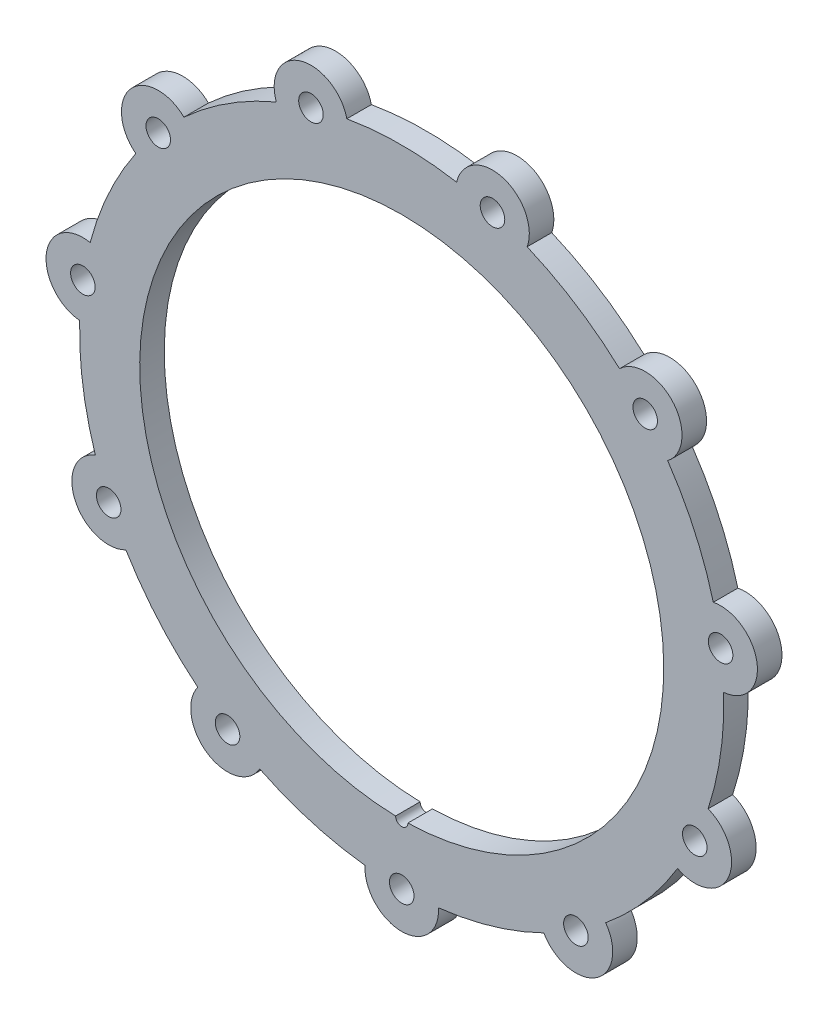
SolidWorks part; units mm, degrees
ref_plane "前视基准面" through (0, 0, 0) normal (0, 0, 1) x (1, 0, 0)
ref_plane "上视基准面" through (0, 0, 0) normal (0, 1, 0) x (1, 0, 0)
ref_plane "右视基准面" through (0, 0, 0) normal (1, 0, 0) x (0, 0, -1)
sketch "草图1" plane through (0, 0, 0) normal (0, 0, 1) x (1, 0, 0)
  line L0 (0, 0) -> (-51.9656, 7.4715) construction
  line L1 (-51.9656, 7.4715) -> (-73.6711, 10.5923) construction
  line L2 (0, 0) -> (-47.7557, -21.8093) construction
  line L3 (-47.7557, -21.8093) -> (-59.3488, -27.1037) construction
  circle A0 centre (0, 0) radius 42.7
  circle A1 centre (0, 0) radius 62.5 construction
  circle A2 centre (0, 0) radius 59 construction
  circle A19 centre (0, 0) radius 52.5 construction
  circle A23 centre (-51.9656, 7.4715) radius 2
  circle A103 centre (-47.7557, -21.8093) radius 6 construction
  circle A104 centre (-51.9656, 7.4715) radius 6 construction
  arc A105 (-57.9046, 8.3254) -> (-52.4788, 1.4935) centre (-51.9656, 7.4715) ccw
  arc A106 (-49.9322, -16.218) -> (-53.2135, -24.3018) centre (-47.7557, -21.8093) ccw
  arc A107 (-49.9322, -16.218) -> (-52.4788, 1.4935) centre (0, 0) cw
  arc A108 (-44.2114, 38.3094) -> (-43.3405, 29.6286) centre (-39.6769, 34.3802) ccw
  arc A109 (-50.7738, 13.352) -> (-43.3405, 29.6286) centre (0, 0) cw
  arc A110 (-50.7738, 13.352) -> (-57.9046, 8.3254) centre (-51.9656, 7.4715) ccw
  circle A111 centre (-39.6769, 34.3802) radius 2
  arc A112 (-16.4814, 56.1303) -> (-20.4419, 48.3568) centre (-14.791, 50.3734) ccw
  arc A113 (-35.495, 38.6828) -> (-20.4419, 48.3568) centre (0, 0) cw
  arc A114 (-35.495, 38.6828) -> (-44.2114, 38.3094) centre (-39.6769, 34.3802) ccw
  circle A115 centre (-14.791, 50.3734) radius 2
  arc A116 (16.4814, 56.1303) -> (8.9468, 51.732) centre (14.791, 50.3734) ccw
  arc A117 (-8.9468, 51.732) -> (8.9468, 51.732) centre (0, 0) cw
  arc A118 (-8.9468, 51.732) -> (-16.4814, 56.1303) centre (-14.791, 50.3734) ccw
  circle A119 centre (14.791, 50.3734) radius 2
  arc A120 (44.2114, 38.3094) -> (35.495, 38.6828) centre (39.6769, 34.3802) ccw
  arc A121 (20.4419, 48.3568) -> (35.495, 38.6828) centre (0, 0) cw
  arc A122 (20.4419, 48.3568) -> (16.4814, 56.1303) centre (14.791, 50.3734) ccw
  circle A123 centre (39.6769, 34.3802) radius 2
  arc A124 (57.9046, 8.3254) -> (50.7738, 13.352) centre (51.9656, 7.4715) ccw
  arc A125 (43.3405, 29.6286) -> (50.7738, 13.352) centre (0, 0) cw
  arc A126 (43.3405, 29.6286) -> (44.2114, 38.3094) centre (39.6769, 34.3802) ccw
  circle A131 centre (51.9656, 7.4715) radius 2
  arc A132 (53.2135, -24.3018) -> (49.9322, -16.218) centre (47.7557, -21.8093) ccw
  arc A133 (52.4788, 1.4935) -> (49.9322, -16.218) centre (0, 0) cw
  arc A134 (52.4788, 1.4935) -> (57.9046, 8.3254) centre (51.9656, 7.4715) ccw
  circle A135 centre (47.7557, -21.8093) radius 2
  arc A136 (31.6275, -49.2133) -> (33.2376, -40.6388) centre (28.3836, -44.1658) ccw
  arc A137 (44.9554, -27.1157) -> (33.2376, -40.6388) centre (0, 0) cw
  circle A191 centre (-47.7557, -21.8093) radius 2 construction
  circle A209 centre (14.791, 50.3734) radius 2 [skipped]
  circle A214 centre (39.6769, 34.3802) radius 2 [skipped]
  circle A220 centre (51.9656, 7.4715) radius 2 [skipped]
  circle A226 centre (47.7557, -21.8093) radius 2 [skipped]
  circle A232 centre (28.3836, -44.1658) radius 2 [skipped]
  circle A238 centre (0, -52.5) radius 2 [skipped]
  arc A243 (44.9554, -27.1157) -> (53.2135, -24.3018) centre (47.7557, -21.8093) ccw
  circle A244 centre (28.3836, -44.1658) radius 2
  arc A245 (0, -58.5) -> (5.9902, -52.1571) centre (0, -52.5) ccw
  arc A246 (23.159, -47.1159) -> (5.9902, -52.1571) centre (0, 0) cw
  arc A247 (23.159, -47.1159) -> (31.6275, -49.2133) centre (28.3836, -44.1658) ccw
  circle A248 centre (0, -52.5) radius 2
  arc A249 (-31.6275, -49.2133) -> (-23.159, -47.1159) centre (-28.3836, -44.1658) ccw
  circle A252 centre (-28.3836, -44.1658) radius 2 [skipped]
  arc A256 (-5.9902, -52.1571) -> (-23.159, -47.1159) centre (0, 0) cw
  circle A261 centre (-39.6769, 34.3802) radius 2 [skipped]
  circle A267 centre (-14.791, 50.3734) radius 2 [skipped]
  arc A269 (-5.9902, -52.1571) -> (0, -58.5) centre (0, -52.5) ccw
  circle A272 centre (-28.3836, -44.1658) radius 2
  arc A273 (-53.2135, -24.3018) -> (-44.9554, -27.1157) centre (-47.7557, -21.8093) ccw
  arc A274 (-33.2376, -40.6388) -> (-44.9554, -27.1157) centre (0, 0) cw
  arc A275 (-33.2376, -40.6388) -> (-31.6275, -49.2133) centre (-28.3836, -44.1658) ccw
  circle A276 centre (-47.7557, -21.8093) radius 2
  dimension "D1" = 85.4
  dimension "D3" = 118
  dimension "D6" = 105
  dimension "D5" = 11
extrude "凸台-拉伸1" add sketch "草图1" along normal blind 4
sketch "草图2" plane through (0, 0, 4) normal (0, 0, 1) x (1, 0, 0)
  circle A0 centre (0, -42.7) radius 1
  circle A1 centre (0, 0) radius 42.7 construction
extrude "切除-拉伸1" cut sketch "草图2" against normal blind 4
equation "\"52.5×2\"=96.9638"
